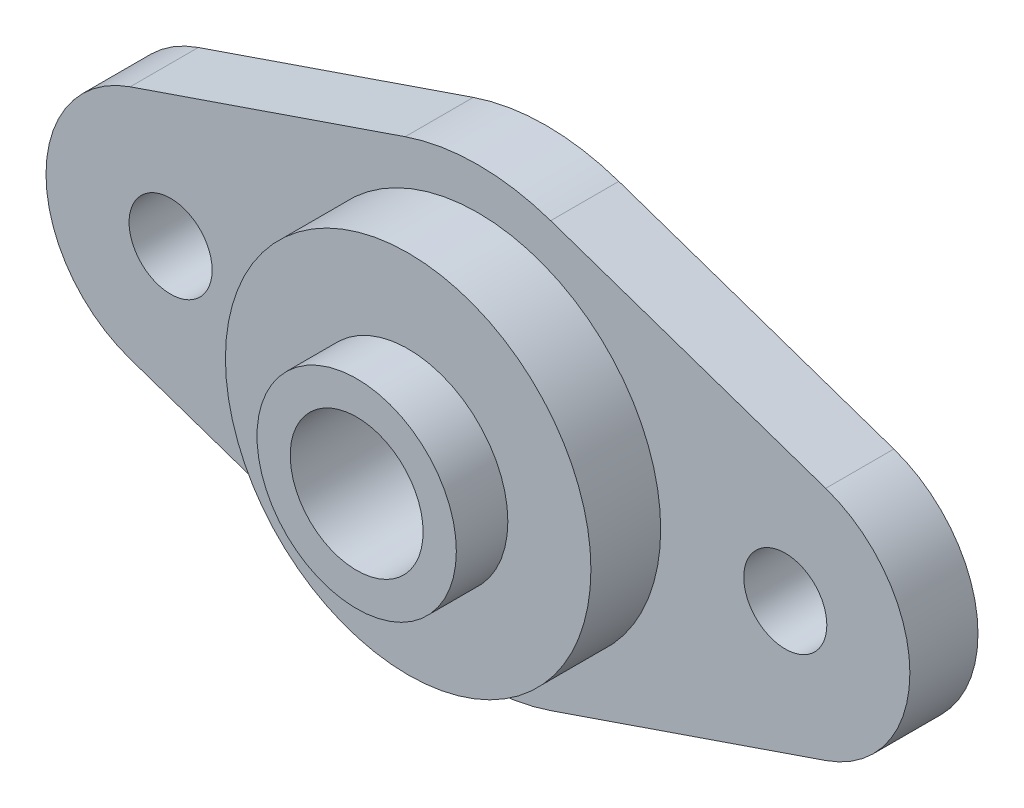
SolidWorks part; units mm, degrees
ref_plane "Front Plane" through (0, 0, 0) normal (0, 0, 1) x (1, 0, 0)
ref_plane "Top Plane" through (0, 0, 0) normal (0, 1, 0) x (1, 0, 0)
ref_plane "Right Plane" through (0, 0, 0) normal (1, 0, 0) x (0, 0, -1)
sketch "Sketch2" plane through (0, 0, 0) normal (0, 0, 1) x (1, 0, 0)
  line L0 (20.9324, 7.0946) -> (4.3784, 12.7703)
  line L1 (20.9324, -7.0946) -> (4.3784, -12.7703)
  line L2 (0, 13.5) -> (0, -13.5) construction
  line L3 (-20.9324, -7.0946) -> (-4.3784, -12.7703)
  line L4 (-20.9324, 7.0946) -> (-4.3784, 12.7703)
  circle A0 centre (0, 0) radius 4
  circle A1 centre (0, 0) radius 13.5
  arc A2 (20.9324, 7.0946) -> (20.9324, -7.0946) centre (18.5, 0) cw
  arc A3 (-20.9324, 7.0946) -> (-20.9324, -7.0946) centre (-18.5, 0) ccw
  circle A4 centre (18.5, 0) radius 2.5
  circle A5 centre (-18.5, 0) radius 2.5
  dimension "D1" = 8
  dimension "D2" = 27
  dimension "D3" = 7.5
  dimension "D5" = 5
  dimension "D4" = 18.5
extrude "Boss-Extrude1" add sketch "Sketch2" along normal blind 4.1 contours L4 A3 L3 A1 | A2 L0 A1 L1 | L2 A1 A0 | A1 L2 A0
sketch "Sketch3" plane through (0, 0, 0) normal (0, 0, 1) x (1, 0, 0)
  circle A0 centre (0, 0) radius 6
  circle A1 centre (0, 0) radius 4
  dimension "D1" = 12
  dimension "D2" = 8
extrude "Boss-Extrude2" add sketch "Sketch3" along normal blind 11.4
ref_plane "Plane1" through (0, 0, 4.1) normal (0, 0, 1) x (1, 0, 0)
sketch "Sketch4" plane through (0, 0, 4.1) normal (0, 0, 1) x (1, 0, 0)
  circle A0 centre (0, 0) radius 11
  circle A1 centre (0, 0) radius 6
  dimension "D1" = 12
  dimension "D2" = 22
extrude "Boss-Extrude3" add sketch "Sketch4" along normal blind 4.2
